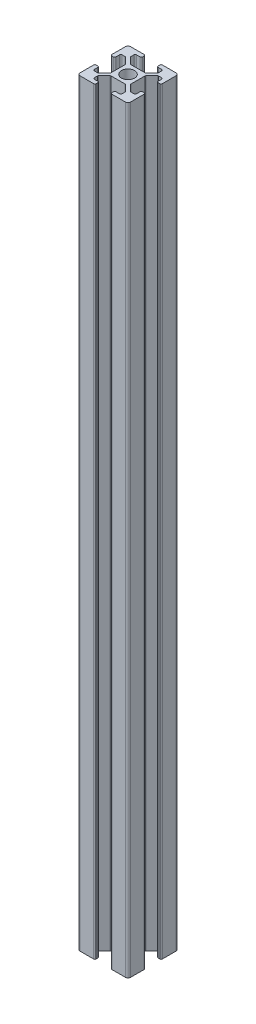
SolidWorks part; units mm, degrees
ref_plane "前视基准面" through (0, 0, 0) normal (0, 0, 1) x (1, 0, 0)
ref_plane "上视基准面" through (0, 0, 0) normal (0, 1, 0) x (1, 0, 0)
ref_plane "右视基准面" through (0, 0, 0) normal (1, 0, 0) x (0, 0, -1)
ref_plane "基准面1" through (0, 170, 0) normal (0, 1, 0) x (1, 0, 0)
sketch "草图1" plane through (0, 170, 0) normal (0, 1, 0) x (1, 0, 0)
  line L0 (-3.1, 8.85) -> (-3.1, 9.5)
  line L1 (-3.6, 10) -> (-9, 10)
  line L2 (-10, 9) -> (-10, 3.6)
  line L3 (-9.5, 3.1) -> (-8.85, 3.1)
  line L4 (-8.35, 3.6) -> (-8.35, 5)
  line L5 (-7.85, 5.5) -> (-6.6263, 5.5)
  line L6 (-6.2728, 5.3536) -> (-4.0464, 3.1272)
  line L7 (-3.9, 2.7737) -> (-3.9, -2.7737)
  line L8 (-4.0464, -3.1272) -> (-6.2728, -5.3536)
  line L9 (-6.6263, -5.5) -> (-7.85, -5.5)
  line L10 (-8.35, -5) -> (-8.35, -3.6)
  line L11 (-8.85, -3.1) -> (-9.5, -3.1)
  line L12 (-10, -3.6) -> (-10, -9)
  line L13 (-9, -10) -> (-3.6, -10)
  line L14 (-3.1, -9.5) -> (-3.1, -8.85)
  line L15 (-3.6, -8.35) -> (-5, -8.35)
  line L16 (-5.5, -7.85) -> (-5.5, -6.6263)
  line L17 (-5.3536, -6.2728) -> (-3.1272, -4.0464)
  line L18 (-2.7737, -3.9) -> (2.7737, -3.9)
  line L19 (3.1272, -4.0464) -> (5.3536, -6.2728)
  line L20 (5.5, -6.6263) -> (5.5, -7.85)
  line L21 (5, -8.35) -> (3.6, -8.35)
  line L22 (3.1, -8.85) -> (3.1, -9.5)
  line L23 (3.6, -10) -> (9, -10)
  line L24 (10, -9) -> (10, -3.6)
  line L25 (9.5, -3.1) -> (8.85, -3.1)
  line L26 (8.35, -3.6) -> (8.35, -5)
  line L27 (7.85, -5.5) -> (6.6263, -5.5)
  line L28 (6.2728, -5.3536) -> (4.0464, -3.1272)
  line L29 (3.9, -2.7737) -> (3.9, 2.7737)
  line L30 (4.0464, 3.1272) -> (6.2728, 5.3536)
  line L31 (6.6263, 5.5) -> (7.85, 5.5)
  line L32 (8.35, 5) -> (8.35, 3.6)
  line L33 (8.85, 3.1) -> (9.5, 3.1)
  line L34 (10, 3.6) -> (10, 9)
  line L35 (9, 10) -> (3.6, 10)
  line L36 (3.1, 9.5) -> (3.1, 8.85)
  line L37 (3.6, 8.35) -> (5, 8.35)
  line L38 (5.5, 7.85) -> (5.5, 6.6263)
  line L39 (5.3536, 6.2728) -> (3.1272, 4.0464)
  line L40 (2.7737, 3.9) -> (-2.7737, 3.9)
  line L41 (-3.1272, 4.0464) -> (-5.5, 6.4192)
  line L42 (-5.5, 6.4192) -> (-5.5, 7.85)
  line L43 (-5, 8.35) -> (-3.6, 8.35)
  circle A0 centre (0, 0) radius 2.6
  arc A1 (-3.1, 9.5) -> (-3.6, 10) centre (-3.6, 9.5) ccw
  arc A2 (-9, 10) -> (-10, 9) centre (-9, 9) ccw
  arc A3 (-10, 3.6) -> (-9.5, 3.1) centre (-9.5, 3.6) ccw
  arc A4 (-8.85, 3.1) -> (-8.35, 3.6) centre (-8.85, 3.6) ccw
  arc A5 (-8.35, 5) -> (-7.85, 5.5) centre (-7.85, 5) cw
  arc A6 (-6.6263, 5.5) -> (-6.2728, 5.3536) centre (-6.6263, 5) cw
  arc A7 (-4.0464, 3.1272) -> (-3.9, 2.7737) centre (-4.4, 2.7737) cw
  arc A8 (-3.9, -2.7737) -> (-4.0464, -3.1272) centre (-4.4, -2.7737) cw
  arc A9 (-6.2728, -5.3536) -> (-6.6263, -5.5) centre (-6.6263, -5) cw
  arc A10 (-7.85, -5.5) -> (-8.35, -5) centre (-7.85, -5) cw
  arc A11 (-8.35, -3.6) -> (-8.85, -3.1) centre (-8.85, -3.6) ccw
  arc A12 (-9.5, -3.1) -> (-10, -3.6) centre (-9.5, -3.6) ccw
  arc A13 (-10, -9) -> (-9, -10) centre (-9, -9) ccw
  arc A14 (-3.6, -10) -> (-3.1, -9.5) centre (-3.6, -9.5) ccw
  arc A15 (-3.1, -8.85) -> (-3.6, -8.35) centre (-3.6, -8.85) ccw
  arc A16 (-5, -8.35) -> (-5.5, -7.85) centre (-5, -7.85) cw
  arc A17 (-5.5, -6.6263) -> (-5.3536, -6.2728) centre (-5, -6.6263) cw
  arc A18 (-3.1272, -4.0464) -> (-2.7737, -3.9) centre (-2.7737, -4.4) cw
  arc A19 (2.7737, -3.9) -> (3.1272, -4.0464) centre (2.7737, -4.4) cw
  arc A20 (5.3536, -6.2728) -> (5.5, -6.6263) centre (5, -6.6263) cw
  arc A21 (5.5, -7.85) -> (5, -8.35) centre (5, -7.85) cw
  arc A22 (3.6, -8.35) -> (3.1, -8.85) centre (3.6, -8.85) ccw
  arc A23 (3.1, -9.5) -> (3.6, -10) centre (3.6, -9.5) ccw
  arc A24 (9, -10) -> (10, -9) centre (9, -9) ccw
  arc A25 (10, -3.6) -> (9.5, -3.1) centre (9.5, -3.6) ccw
  arc A26 (8.85, -3.1) -> (8.35, -3.6) centre (8.85, -3.6) ccw
  arc A27 (8.35, -5) -> (7.85, -5.5) centre (7.85, -5) cw
  arc A28 (6.6263, -5.5) -> (6.2728, -5.3536) centre (6.6263, -5) cw
  arc A29 (4.0464, -3.1272) -> (3.9, -2.7737) centre (4.4, -2.7737) cw
  arc A30 (3.9, 2.7737) -> (4.0464, 3.1272) centre (4.4, 2.7737) cw
  arc A31 (6.2728, 5.3536) -> (6.6263, 5.5) centre (6.6263, 5) cw
  arc A32 (7.85, 5.5) -> (8.35, 5) centre (7.85, 5) cw
  arc A33 (8.35, 3.6) -> (8.85, 3.1) centre (8.85, 3.6) ccw
  arc A34 (9.5, 3.1) -> (10, 3.6) centre (9.5, 3.6) ccw
  arc A35 (10, 9) -> (9, 10) centre (9, 9) ccw
  arc A36 (3.6, 10) -> (3.1, 9.5) centre (3.6, 9.5) ccw
  arc A37 (3.1, 8.85) -> (3.6, 8.35) centre (3.6, 8.85) ccw
  arc A38 (5, 8.35) -> (5.5, 7.85) centre (5, 7.85) cw
  arc A39 (5.5, 6.6263) -> (5.3536, 6.2728) centre (5, 6.6263) cw
  arc A40 (3.1272, 4.0464) -> (2.7737, 3.9) centre (2.7737, 4.4) cw
  arc A41 (-2.7737, 3.9) -> (-3.1272, 4.0464) centre (-2.7737, 4.4) cw
  arc A42 (-5.5, 7.85) -> (-5, 8.35) centre (-5, 7.85) cw
  arc A43 (-3.6, 8.35) -> (-3.1, 8.85) centre (-3.6, 8.85) ccw
extrude "凸台-拉伸2" add sketch "草图1" along normal blind 300
